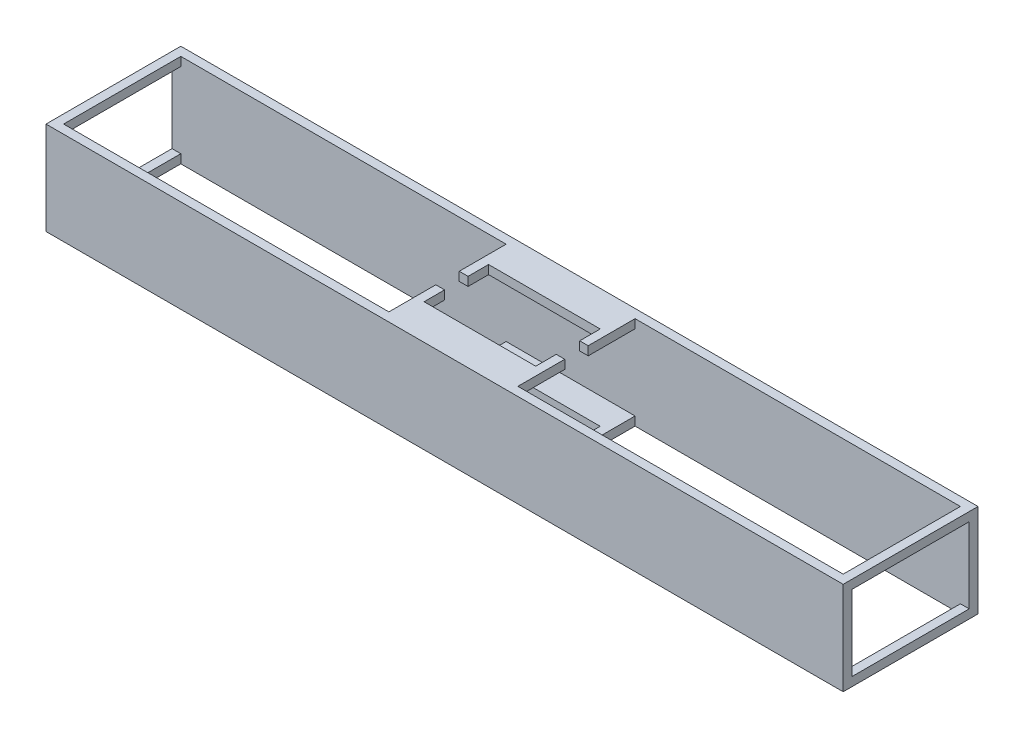
SolidWorks part; units mm, degrees
ref_plane "Front Plane" through (0, 0, 0) normal (0, 0, 1) x (1, 0, 0)
ref_plane "Top Plane" through (0, 0, 0) normal (0, 1, 0) x (1, 0, 0)
ref_plane "Right Plane" through (0, 0, 0) normal (1, 0, 0) x (0, 0, -1)
sketch "Sketch1" plane through (0, 0, 0) normal (0, 1, 0) x (1, 0, 0)
  line L1 (-34, -5.75) -> (34, -5.75)
  line L2 (-34, -5.75) -> (-34, 5.75)
  line L3 (-34, 5.75) -> (34, 5.75)
  line L4 (34, -5.75) -> (34, 5.75)
  line L5 (-34, -5.75) -> (34, 5.75) construction
  line L6 (-34, 5.75) -> (34, -5.75) construction
  point P0 (0, 0)
  dimension "D1" = 68
  dimension "D2" = 11.5
extrude "Boss-Extrude1" add sketch "Sketch1" along normal blind 7.94
sketch "Sketch2" plane through (0, 7.94, 0) normal (0, 1, 0) x (1, 0, 0)
  line L0 (34, 5.75) -> (-34, 5.75) construction
  line L1 (-33.25, 5) -> (-5.5, 5)
  line L2 (-33.25, 5) -> (-33.25, -5)
  line L3 (-33.25, -5) -> (-5.5, -5)
  line L4 (-5.5, 5) -> (-5.5, -5)
  line L5 (5.5, 5) -> (33.25, 5)
  line L6 (5.5, 5) -> (5.5, -5)
  line L7 (5.5, -5) -> (33.25, -5)
  line L8 (33.25, 5) -> (33.25, -5)
  line L9 (-4.75, 2.75) -> (4.775, 2.75)
  line L10 (-4.75, 2.75) -> (-4.75, -2.75)
  line L11 (-4.75, -2.75) -> (4.775, -2.75)
  line L12 (4.775, 2.75) -> (4.775, -2.75)
  line L14 (-34, 5.75) -> (-34, -5.75) construction
  line L15 (34, -5.75) -> (34, 5.75) construction
  dimension "D1" = 10
  dimension "D2" = 10
  dimension "D3" = 3
  dimension "D4" = 0.75
  dimension "D5" = 0.75
  dimension "D6" = 9.525
  dimension "D7" = 29.25
  dimension "D8" = 27.75
  dimension "D9" = 0.75
  dimension "D10" = 27.75
  dimension "D11" = 0.75
  dimension "D12" = 5.5
extrude "Cut-Extrude1" cut sketch "Sketch2" against normal through all
sketch "Sketch3" plane through (-34, 0, 0) normal (-1, 0, 0) x (0, 0, 1)
  line L0 (-5.75, 7.94) -> (-5.75, 0) construction
  line L1 (-5, 7.19) -> (5, 7.19)
  line L2 (-5, 7.19) -> (-5, 0.75)
  line L3 (-5, 0.75) -> (5, 0.75)
  line L4 (5, 7.19) -> (5, 0.75)
  line L6 (-5.75, 7.94) -> (5.75, 7.94) construction
  dimension "D1" = 0.75
  dimension "D2" = 10
  dimension "D3" = 0.75
  dimension "D4" = 6.44
extrude "Cut-Extrude2" cut sketch "Sketch3" against normal through all
sketch "Sketch4" plane through (0, 7.94, 0) normal (0, 1, 0) x (1, 0, 0)
  line L0 (-5.5, -5) -> (-5.5, 5) construction
  line L1 (-5.5, 1) -> (5.5, 1)
  line L2 (-5.5, 1) -> (-5.5, -1)
  line L3 (-5.5, -1) -> (5.5, -1)
  line L4 (5.5, 1) -> (5.5, -1)
  line L5 (5.5, 5) -> (5.5, -5) construction
  line L6 (34, 5.75) -> (-34, 5.75) construction
  dimension "D1" = 2
  dimension "D2" = 4.75
extrude "Cut-Extrude3" cut sketch "Sketch4" against normal blind 2.5
